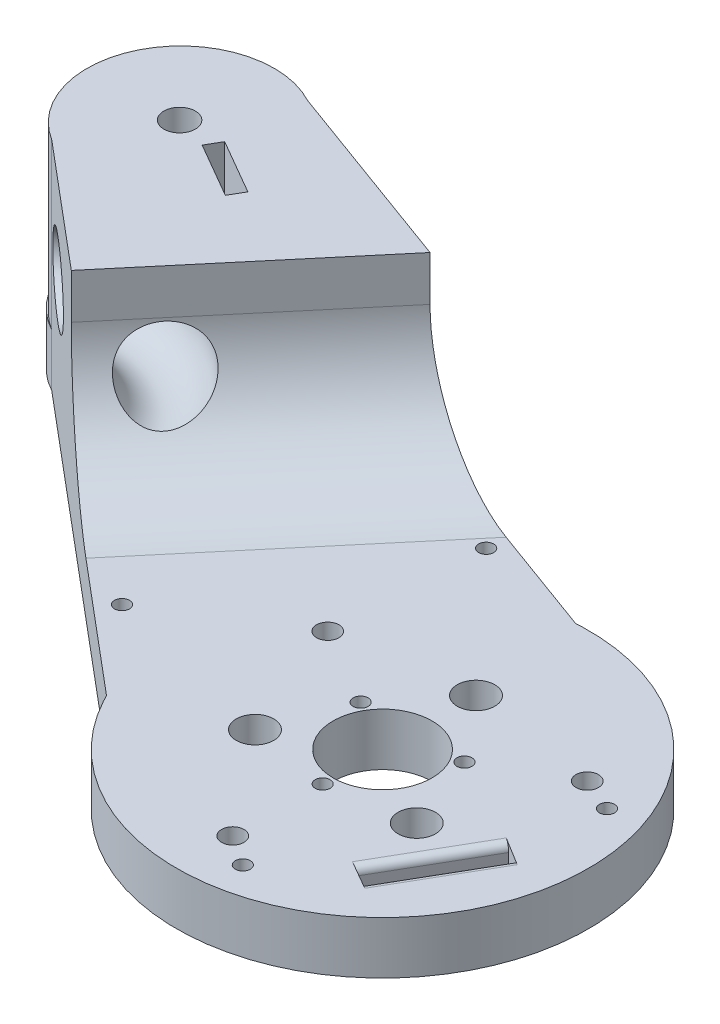
SolidWorks part; units mm, degrees
ref_plane "前视基准面" through (0, 0, 0) normal (0, 0, 1) x (1, 0, 0)
ref_plane "上视基准面" through (0, 0, 0) normal (0, 1, 0) x (1, 0, 0)
ref_plane "右视基准面" through (0, 0, 0) normal (1, 0, 0) x (0, 0, -1)
sketch "草图1" plane through (0, 0, 0) normal (0, 1, 0) x (1, 0, 0)
  line L0 (0, 0) -> (-10.8, -18.7061) construction
  line L1 (-10.8, -18.7061) -> (10.8, -18.7061) construction
  line L2 (10.8, -18.7061) -> (0, 0) construction
  line L3 (-10.8, -18.7061) -> (5.4, -9.3531) construction
  line L4 (10.8, -18.7061) -> (-5.4, -9.3531) construction
  circle A0 centre (0, -12.4708) radius 27.5
  circle A1 centre (0, -12.4708) radius 6.6
  circle A2 centre (-10.8, -18.7061) radius 1.3
  circle A3 centre (10.8, -18.7061) radius 1.3
  circle A4 centre (0, 0) radius 1.3
  dimension "D4" = 55
  dimension "D5" = 13.2
  dimension "D6" = 2.6
  dimension "D7" = 2.6
  dimension "D8" = 2.6
  dimension "D1" = 21.6
  dimension "D2" = 21.6
  dimension "D3" = 21.6
extrude "凸台-拉伸1" add sketch "草图1" along normal blind 7
sketch "草图2" plane through (0, 7, 0) normal (0, 1, 0) x (1, 0, 0)
  circle A0 centre (-10.8, -18.7061) radius 2.5
  circle A1 centre (10.8, -18.7061) radius 2.5
  circle A2 centre (0, 0) radius 2.5
  dimension "D1" = 5
  dimension "D2" = 5
  dimension "D3" = 5
extrude "切除-拉伸2" cut sketch "草图2" against normal blind 5
sketch "草图4" plane through (0, 7, 0) normal (0, 1, 0) x (1, 0, 0)
  line L0 (0, 0) -> (-10.8, -18.7061) construction
  line L1 (0, -12.4708) -> (-23.8157, 1.2792) construction
  line L2 (0, -2.4708) -> (0, -22.4708) construction
  circle A1 centre (0, -12.4708) radius 27.5 construction
  circle A2 centre (-6.9282, -8.4708) radius 1
  circle A3 centre (6.9282, -8.4708) radius 1
  circle A4 centre (0, -20.4708) radius 1
  dimension "D3" = 2
  dimension "D5" = 2
  dimension "D2" = 8
  dimension "D4" = 8
extrude "切除-拉伸3" cut sketch "草图4" against normal blind 6
sketch "草图5" plane through (0, 7, 0) normal (0, 1, 0) x (1, 0, 0)
  line L0 (0, -12.4708) -> (-6.9282, -8.4708) construction
  line L1 (-6.9282, -8.4708) -> (-23.8157, 1.2792) construction
  line L4 (0, -12.4708) -> (0, -20.4708) construction
  line L5 (0, -20.4708) -> (0, -39.9708) construction
  line L6 (0, -12.4708) -> (-17.3205, -2.4708) construction
  line L7 (0, -12.4708) -> (17.3205, -2.4708) construction
  circle A0 centre (0, -12.4708) radius 27.5 construction
  circle A5 centre (0, -12.4708) radius 20 construction
  circle A6 centre (-17.3205, -2.4708) radius 1.5
  circle A7 centre (0, -32.4708) radius 1.5
  circle A8 centre (17.3205, -2.4708) radius 1.5
  dimension "D1" = 3
  dimension "D2" = 3
  dimension "D4" = 40
  dimension "D5" = 3
extrude "切除-拉伸4" cut sketch "草图5" against normal through all
sketch "草图6" plane through (0, 0, 0) normal (0, -1, 0) x (1, 0, 0)
  line L1 (3.2909, 32.4708) -> (1.6454, 35.3208)
  line L2 (1.6454, 35.3208) -> (-1.6454, 35.3208)
  line L3 (-1.6454, 35.3208) -> (-3.2909, 32.4708)
  line L4 (-3.2909, 32.4708) -> (-1.6454, 29.6208)
  line L5 (-1.6454, 29.6208) -> (1.6454, 29.6208)
  line L6 (1.6454, 29.6208) -> (3.2909, 32.4708)
  line L7 (20.6114, 2.4708) -> (18.966, 5.3208)
  line L8 (18.966, 5.3208) -> (15.6751, 5.3208)
  line L9 (15.6751, 5.3208) -> (14.0296, 2.4708)
  line L10 (14.0296, 2.4708) -> (15.6751, -0.3792)
  line L11 (15.6751, -0.3792) -> (18.966, -0.3792)
  line L12 (18.966, -0.3792) -> (20.6114, 2.4708)
  line L13 (-14.0296, 2.4708) -> (-15.6751, 5.3208)
  line L14 (-15.6751, 5.3208) -> (-18.966, 5.3208)
  line L15 (-18.966, 5.3208) -> (-20.6114, 2.4708)
  line L16 (-20.6114, 2.4708) -> (-18.966, -0.3792)
  line L17 (-18.966, -0.3792) -> (-15.6751, -0.3792)
  line L18 (-15.6751, -0.3792) -> (-14.0296, 2.4708)
  circle A3 centre (0, 32.4708) radius 2.85 construction
  circle A4 centre (17.3205, 2.4708) radius 2.85 construction
  circle A5 centre (-17.3205, 2.4708) radius 2.85 construction
  dimension "D1" = 5.7
  dimension "D2" = 5.7
  dimension "D3" = 5.7
extrude "切除-拉伸5" cut sketch "草图6" against normal blind 2.7
sketch "草图7" plane through (0, 7, 0) normal (0, 1, 0) x (1, 0, 0)
  line L0 (0, -12.4708) -> (15.5885, -21.4708) construction
  line L1 (19.3385, -14.9756) -> (11.8385, -27.966)
  line L2 (11.8385, -27.966) -> (14.0035, -29.216)
  line L3 (14.0035, -29.216) -> (21.4688, -16.2858)
  line L4 (21.4688, -16.2858) -> (19.3385, -14.9756)
  dimension "D1" = 18
  dimension "D2" = 7.5
  dimension "D3" = 2.5
extrude "切除-拉伸6" cut sketch "草图7" against normal blind 10
fillet "圆角1" radius 1 4 edges at (17.7361, 7, 22.7509) (15.5885, 7, 21.4708) (17.7361, 0, 22.7509) (15.5885, 0, 21.4708)
sketch "草图9" plane through (0, 0, 0) normal (0, -1, 0) x (1, 0, 0)
  line L0 (18.5952, 23.2629) -> (-23.7845, -1.3331) construction
  line L1 (14.8695, 29.716) -> (22.3209, 16.8099) construction
  line L2 (-24.6378, 24.6867) -> (-70.5631, -13.9249)
  line L3 (-24.6378, 24.6867) -> (-1.6865, -14.9775) construction
  line L4 (-70.5631, -13.9249) -> (-58.0482, -35.5532) construction
  line L5 (-58.0482, -35.5532) -> (-1.6865, -14.9775)
  line L6 (-24.6378, 24.6867) -> (-24.1982, 25.5358)
  line L7 (-24.1982, 25.5358) -> (-27.3768, 9.8707)
  line L8 (-27.3768, 9.8707) -> (-16.9808, -9.1603)
  line L9 (-16.9808, -9.1603) -> (-0.825, -15.0169)
  line L10 (-0.825, -15.0169) -> (-1.6865, -14.9775)
  line L11 (-62.703, -27.5088) -> (-46.5749, -18.1764) construction
  line L12 (-62.703, -27.5088) -> (-58.808, -25.255) construction
  line L13 (-58.808, -25.255) -> (-51.4509, -20.9979)
  line L14 (-51.4509, -20.9979) -> (-52.5528, -19.0937)
  line L15 (-52.5528, -19.0937) -> (-59.9099, -23.3508)
  line L16 (-59.9099, -23.3508) -> (-58.808, -25.255)
  arc A0 (-70.5631, -13.9249) -> (-58.0482, -35.5532) centre (-64.6392, -24.9321) ccw
  circle A1 centre (0, 12.4708) radius 27.5 construction
  circle A2 centre (-64.3056, -24.7391) radius 2.1
  point P19 (0, 0)
  dimension "D4" = 12.5
  dimension "D5" = 4.2
  dimension "D6" = 3.2
  dimension "D1" = 60
  dimension "D2" = 80
  dimension "D3" = 80
  dimension "D7" = 4.5
  dimension "D8" = 2.2
  dimension "D9" = 2.2
  dimension "D10" = 8.5
extrude "凸台-拉伸3" add sketch "草图9" against normal blind 7
sketch "草图13" plane through (0, 7, 0) normal (0, 1, 0) x (1, 0, 0)
  line L0 (21.8248, -4.3359) -> (-16.341, 17.6991) construction
  line L1 (-16.341, 17.6991) -> (-34.136, -13.1228) construction
  line L2 (-34.136, -13.1228) -> (4.0298, -35.1578) construction
  line L3 (4.0298, -35.1578) -> (21.8248, -4.3359) construction
  line L4 (10.9724, -27.466) -> (18.4863, -14.4515) construction
  circle A0 centre (4.0298, -35.1578) radius 1
  circle A1 centre (21.8248, -4.3359) radius 1
  circle A2 centre (-16.341, 17.6991) radius 1
  circle A3 centre (-34.136, -13.1228) radius 1
  dimension "D3" = 2
  dimension "D4" = 2
  dimension "D5" = 2
  dimension "D6" = 2
  dimension "D1" = 35.59
  dimension "D2" = 44.07
extrude "切除-拉伸9" cut sketch "草图13" against normal through all
sketch "草图14" plane through (0, 7, 0) normal (0, 1, 0) x (1, 0, 0)
  line L0 (-70.5631, 13.9249) -> (-54.1546, 0.1295)
  line L1 (-24.6378, -24.6867) -> (-70.5631, 13.9249) construction
  line L2 (-54.1546, 0.1295) -> (-32.2809, 26.1464)
  line L3 (-58.0482, 35.5532) -> (-1.6865, 14.9775) construction
  line L4 (-58.0482, 35.5532) -> (-32.2809, 26.1464)
  line L5 (-58.808, 25.255) -> (-59.9099, 23.3508)
  line L6 (-59.9099, 23.3508) -> (-52.5528, 19.0937)
  line L7 (-52.5528, 19.0937) -> (-51.4509, 20.9979)
  line L8 (-51.4509, 20.9979) -> (-58.808, 25.255)
  arc A0 (-58.0482, 35.5532) -> (-70.5631, 13.9249) centre (-63.972, 24.546) ccw
  circle A1 centre (-64.3056, 24.7391) radius 2.1
extrude "凸台-拉伸4" add sketch "草图14" along normal blind 22
fillet "圆角2" radius 16 1 edges at (-43.2177, 7, -13.1379)
sketch "草图15" plane through (-3.8033, 0, 6.5729) normal (-0.5008, 0, 0.8655) x (0.8655, 0, 0.5008)
  circle A0 centre (-54.4168, 23.6652) radius 1.5
  dimension "D1" = 3
extrude "切除-拉伸10" cut sketch "草图15" against normal through all
sketch "草图16" plane through (4.6264, 0, -12.6729) normal (0.3429, 0, -0.9394) x (-0.9394, 0, -0.3429)
  circle A0 centre (53.0383, 23.6652) radius 3
  dimension "D1" = 6
extrude "切除-拉伸11" cut sketch "草图16" against normal blind 3
sketch "草图17" plane through (-31.7914, 0, -26.7286) normal (0.7654, 0, 0.6435) x (0.6435, 0, -0.7654)
  line L1 (-42.584, 24.0208) -> (-42.584, 8.1547) construction
  circle A0 centre (-25.9012, 17.597) radius 5
  dimension "D1" = 10
revolve "切除-旋转1" cut sketch "草图17" angle 360 about L1
